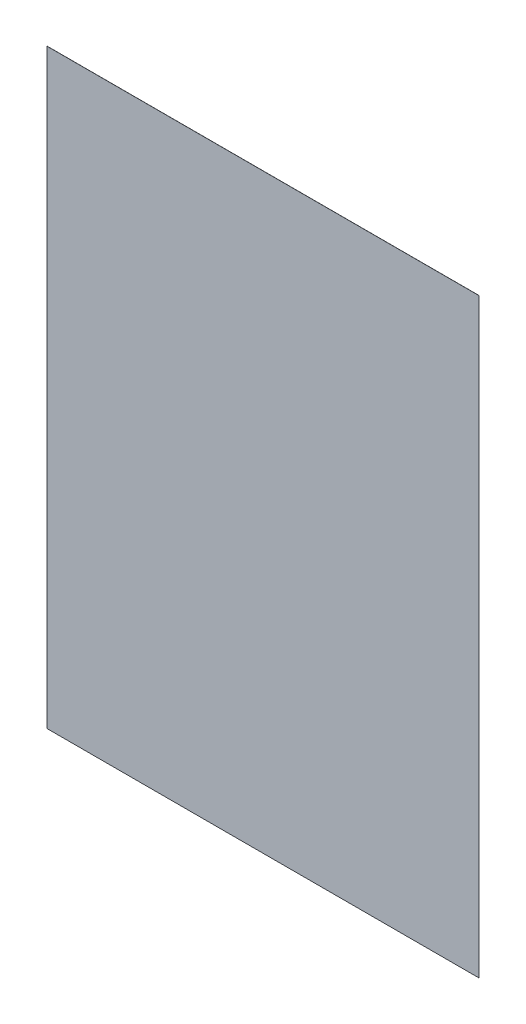
SolidWorks part; units mm, degrees
ref_plane "Front Plane" through (0, 0, 0) normal (0, 0, 1) x (1, 0, 0)
ref_plane "Top Plane" through (0, 0, 0) normal (0, 1, 0) x (1, 0, 0)
ref_plane "Right Plane" through (0, 0, 0) normal (1, 0, 0) x (0, 0, -1)
sketch "Sketch1" plane through (0, 0, 0) normal (0, 0, 1) x (1, 0, 0)
  line L1 (-640, 875) -> (640, 875)
  line L2 (-640, 875) -> (-640, -875)
  line L3 (-640, -875) -> (640, -875)
  line L4 (640, 875) -> (640, -875)
  line L5 (-640, 875) -> (640, -875) construction
  line L6 (-640, -875) -> (640, 875) construction
  point P0 (0, 0)
  dimension "D1" = 1750
  dimension "D2" = 1280
extrude "Boss-Extrude1" add sketch "Sketch1" along normal blind 0.3556
